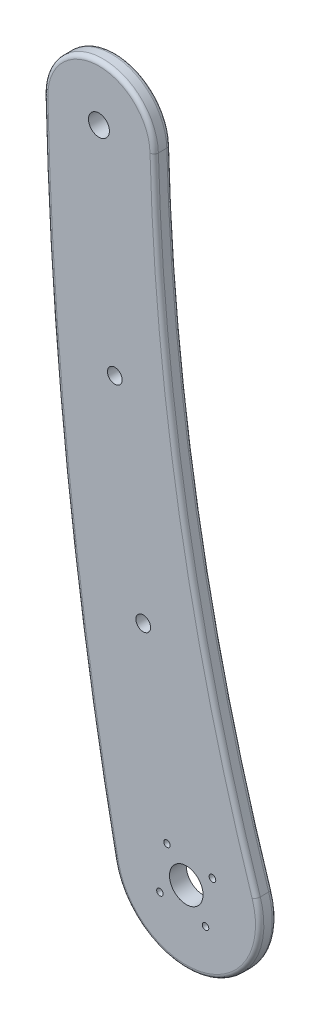
SolidWorks part; units mm, degrees
ref_plane "Front Plane" through (0, 0, 0) normal (0, 0, 1) x (1, 0, 0)
ref_plane "Top Plane" through (0, 0, 0) normal (0, 1, 0) x (1, 0, 0)
ref_plane "Right Plane" through (0, 0, 0) normal (1, 0, 0) x (0, 0, -1)
sketch "Sketch1" plane through (0, 0, 0) normal (0, 0, 1) x (1, 0, 0)
  line L0 (0, 0) -> (0, 28420.5788) construction
  line L1 (0, 0) -> (-28420.5788, 0) construction
  line L2 (-23, 10) -> (-28, 10)
  line L3 (-23, 0) -> (23, 0)
  line L4 (-23, 0) -> (-23, 10)
  line L5 (-23, 10) -> (23, 10) construction
  line L6 (23, 0) -> (23, 10)
  line L7 (-28, 10) -> (-41.8608, 50.4677)
  line L8 (-24.6313, 80.3256) -> (15.2446, 88.1625)
  line L9 (23, 10) -> (28, 10)
  line L10 (28, 10) -> (39.4051, 19.57)
  line L11 (39.4051, 19.57) -> (39.4051, 38.57)
  line L12 (39.4051, 38.57) -> (22.9346, 83.8223)
  line L13 (-20.22, 57.88) -> (-41.0516, 204.4066) construction
  line L14 (16.5541, 81.5) -> (-4.2776, 228.0266) construction
  line L15 (-75.8246, 230.8844) -> (-41.0516, 204.4066) construction
  line L16 (-41.0516, 204.4066) -> (-4.2776, 228.0266) construction
  line L17 (-4.2776, 228.0266) -> (-75.8246, 230.8844) construction
  line L18 (-75.8246, 230.8844) -> (-226.1828, 176.1814) construction
  line L19 (-204.7956, 140.0346) -> (9.2044, 224.1635) construction
  line L20 (-226.1828, 176.1814) -> (-204.7956, 140.0346) construction
  line L21 (-204.7956, 140.0346) -> (-256.0612, 159.9555) construction
  line L22 (-256.0612, 159.9555) -> (-226.1828, 176.1814) construction
  line L23 (-20.22, 57.88) -> (33.1708, 65.9687)
  line L24 (33.1708, 65.9687) -> (9.2044, 224.1635)
  circle A0 centre (-20.22, 57.88) radius 22.875 construction
  circle A1 centre (16.5541, 81.5) radius 6.79 construction
  arc A2 (-41.8608, 50.4677) -> (-24.6313, 80.3256) centre (-20.22, 57.88) cw
  arc A3 (15.2446, 88.1625) -> (22.9346, 83.8223) centre (16.5541, 81.5) cw
  circle A4 centre (-20.22, 57.88) radius 17.5 construction
  circle A5 centre (16.5541, 81.5) radius 7.5 construction
  circle A6 centre (-41.0516, 204.4066) radius 13.1881 construction
  circle A7 centre (-4.2776, 228.0266) radius 8.7345 construction
  circle A8 centre (-75.8246, 230.8844) radius 8.7345 construction
  circle A9 centre (-226.1828, 176.1814) radius 8.1525 construction
  circle A10 centre (-204.7956, 140.0346) radius 9.1166 construction
  dimension "D7" = 45.75
  dimension "D8" = 13.58
  dimension "D14" = 35
  dimension "D15" = 15
  dimension "D1" = 46
  dimension "D2" = 10
  dimension "D3" = 57.88
  dimension "D4" = 20.22
  dimension "D5" = 16.5541
  dimension "D6" = 81.5
  dimension "D9" = 5
  dimension "D10" = 5
  dimension "D11" = 140
  dimension "D12" = 19
  dimension "D13" = 160
  dimension "D16" = 148
  dimension "D17" = 110
  dimension "D18" = 160
  dimension "D19" = 54
  dimension "D20" = 214
  dimension "D21" = 42
  dimension "D22" = 34
  dimension "D23" = 55
  dimension "D24" = 54
  dimension "D25" = 160
sketch "Sketch2" plane through (0, 0, 0) normal (0, 0, 1) x (1, 0, 0)
  line L0 (39.4051, 38.57) -> (22.9346, 83.8223) construction
  line L1 (39.4051, 19.57) -> (39.4051, 38.57) construction
  line L2 (28, 10) -> (39.4051, 19.57) construction
  line L3 (23, 10) -> (28, 10) construction
  line L4 (23, 0) -> (23, 10) construction
  line L5 (-23, 0) -> (23, 0) construction
  line L6 (-23, 0) -> (-23, 10) construction
  line L7 (-23, 10) -> (-28, 10) construction
  line L8 (-28, 10) -> (-41.8608, 50.4677) construction
  line L9 (-24.6313, 80.3256) -> (15.2446, 88.1625) construction
  line L10 (39.4051, 38.57) -> (22.9346, 83.8223)
  line L11 (39.4051, 19.57) -> (39.4051, 38.57)
  line L12 (28, 10) -> (39.4051, 19.57)
  line L13 (23, 10) -> (28, 10)
  line L14 (23, 0) -> (23, 10)
  line L15 (-23, 0) -> (23, 0)
  line L16 (-23, 0) -> (-23, 10)
  line L17 (-23, 10) -> (-28, 10)
  line L18 (-28, 10) -> (-41.8608, 50.4677)
  line L19 (-24.6313, 80.3256) -> (15.2446, 88.1625)
  line L20 (-21.6935, 66.2364) -> (-28.5764, 56.4065)
  line L21 (-21.6935, 66.2364) -> (-2.853, 53.0441)
  line L22 (-28.5764, 56.4065) -> (-9.7359, 43.2143)
  line L23 (-2.853, 53.0441) -> (-9.7359, 43.2143)
  line L24 (-38.9581, 71.0006) -> (37.1704, 17.6948) construction
  line L25 (0, -200000) -> (0, 228420.5788) construction
  arc A0 (22.9346, 83.8223) -> (15.2446, 88.1625) centre (16.5541, 81.5) ccw construction
  arc A1 (-24.6313, 80.3256) -> (-41.8608, 50.4677) centre (-20.22, 57.88) ccw construction
  arc A2 (22.9346, 83.8223) -> (15.2446, 88.1625) centre (16.5541, 81.5) ccw
  arc A3 (-24.6313, 80.3256) -> (-41.8608, 50.4677) centre (-20.22, 57.88) ccw
  circle A4 centre (-27.1828, 62.7554) radius 1
  circle A5 centre (-4.2465, 46.6953) radius 1
  circle A6 centre (17, 5.25) radius 1.75
  circle A7 centre (-17, 5.25) radius 1.75
  circle A8 centre (34.1551, 29.07) radius 1.75
  circle A9 centre (-21.5, 29.07) radius 1.75
  circle A10 centre (16.5541, 81.5) radius 1.75
  point P35 (39.4051, 29.07)
  dimension "D5" = 2
  dimension "D6" = 2
  dimension "D10" = 3.5
  dimension "D1" = 23
  dimension "D2" = 12
  dimension "D3" = 6
  dimension "D4" = 35
  dimension "D7" = 2.5
  dimension "D8" = 2.5
  dimension "D9" = 6
  dimension "D11" = 5.25
  dimension "D12" = 5.25
  dimension "D13" = 6
  dimension "D14" = 6
  dimension "D15" = 21.5
sketch "Sketch4" plane through (0, 0, 0) normal (0, 0, 1) x (1, 0, 0)
  line L0 (-20.22, 57.88) -> (-41.0516, 204.4066) construction
  line L1 (-20.22, 57.88) -> (-41.0516, 204.4066) construction
  circle A0 centre (-41.0516, 204.4066) radius 13.1881 construction
  circle A1 centre (-20.22, 57.88) radius 17.5 construction
  circle A2 centre (-41.0516, 204.4066) radius 13.1881 construction
  circle A3 centre (-20.22, 57.88) radius 17.5 construction
  circle A4 centre (-20.22, 57.88) radius 4
  circle A5 centre (-41.0516, 204.4066) radius 2.5
  arc A6 (-37.3679, 54.3872) -> (-54.2361, 204.0972) centre (795.53, 224.0373) cw
  arc A7 (-27.8679, 204.7498) -> (-3.5761, 63.2867) centre (471.9627, 217.7626) ccw
  arc A8 (-20.22, 57.88) -> (-41.0516, 204.4066) centre (708.2745, 236.1938) cw
  arc A9 (-54.2361, 204.0972) -> (-27.8679, 204.7498) centre (-41.0516, 204.4066) cw
  arc A10 (-37.3679, 54.3872) -> (-3.5761, 63.2867) centre (-20.22, 57.88) ccw
  circle A12 centre (-37.2685, 154.5499) radius 1.75
  circle A13 centre (-30.4821, 106.8156) radius 1.75
  dimension "D1" = 5
  dimension "D2" = 8
  dimension "D3" = 500
  dimension "D4" = 750
  dimension "D5" = 850
  dimension "D6" = 3.5
  dimension "D8" = 3.5
  dimension "D7" = 50
  dimension "D9" = 50
extrude "Boss-Extrude2" add sketch "Sketch4" along normal mid plane 4 separate body
fillet "Fillet3" radius 1 8 edges at (-41.3779, 217.5907, -2) (-49.1254, 128.8678, -2) (-15.7631, 40.957, -2) (-41.3779, 217.5907, 2) (-49.1254, 128.8678, 2) (-15.7631, 40.957, 2) (-20.8246, 133.142, -2) (-20.8246, 133.142, 2)
sketch "Sketch5" plane through (0, 0, -2) normal (0, 0, -1) x (-1, 0, 0)
  circle A0 centre (24.8274, 64.1085) radius 0.7811
sketch "Sketch6" plane through (0, 0, -2) normal (0, 0, -1) x (-1, 0, 0)
  circle A0 centre (24.8145, 64.1519) radius 0.7679
  circle A1 centre (26.5152, 53.2993) radius 0.7718
  circle A2 centre (15.6278, 51.6359) radius 0.768
  circle A3 centre (13.9848, 62.4262) radius 0.7953
extrude "Cut-Extrude1" cut sketch "Sketch6" against normal through all both and the other way through all
